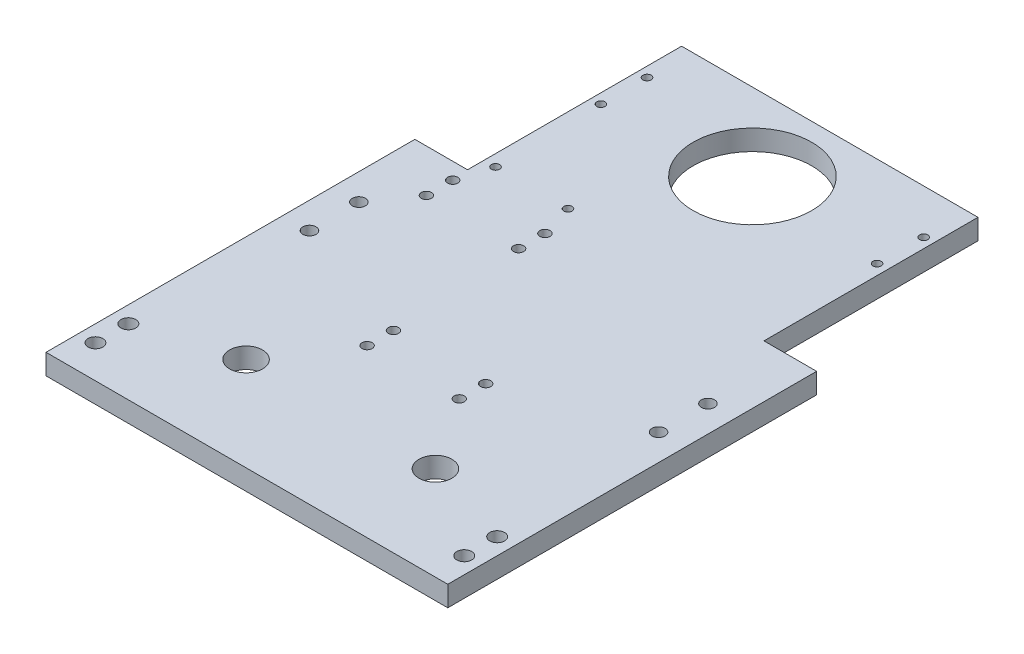
SolidWorks part; units mm, degrees
ref_plane "Front Plane" through (0, 0, 0) normal (0, 0, 1) x (1, 0, 0)
ref_plane "Top Plane" through (0, 0, 0) normal (0, 1, 0) x (1, 0, 0)
ref_plane "Right Plane" through (0, 0, 0) normal (1, 0, 0) x (0, 0, -1)
sketch "Sketch1" plane through (0, 0, 0) normal (0, 1, 0) x (1, 0, 0)
  line L1 (-61, 56) -> (61, 56)
  line L2 (-61, 56) -> (-61, -56)
  line L3 (-61, -56) -> (61, -56)
  line L4 (61, 56) -> (61, -56)
  line L5 (-61, 56) -> (61, -56) construction
  line L6 (-61, -56) -> (61, 56) construction
  point P0 (0, 0)
  dimension "D1" = 122
  dimension "D2" = 112
extrude "Boss-Extrude1" add sketch "Sketch1" along normal blind 6.2
sketch "Sketch2" plane through (0, 0, 0) normal (0, 1, 0) x (1, 0, 0)
  line L0 (61, 56) -> (-61, 56) construction
  line L1 (-45, 56) -> (45, 56)
  line L2 (-45, 56) -> (-45, 121)
  line L3 (-45, 121) -> (45, 121)
  line L4 (45, 56) -> (45, 121)
  line L5 (0, -55) -> (0, 55) construction
  dimension "D1" = 90
  dimension "D2" = 45
  dimension "D3" = 65
extrude "Boss-Extrude2" add sketch "Sketch2" along normal blind 6.2
sketch "Sketch3" plane through (0, 6.2, 0) normal (0, 1, 0) x (1, 0, 0)
  line L0 (-45, 56) -> (45, 56) construction
  line L1 (-45, 121) -> (-45, 56) construction
  line L2 (45, 56) -> (45, 121) construction
  line L3 (0, -3.41) -> (0, 3.41) construction
  circle A0 centre (-41.5, 61) radius 1.25
  circle A1 centre (-19.5, 61) radius 1.25
  circle A2 centre (-42, 93.5) radius 1.25
  circle A3 centre (-42, 107.5) radius 1.25
  circle A4 centre (42, 107.5) radius 1.25
  circle A5 centre (41.8595, 93.5) radius 1.25
  circle A6 centre (0, 97.5) radius 18
  dimension "D1" = 2.5
  dimension "D2" = 2.5
  dimension "D8" = 2.5
  dimension "D13" = 2.5
  dimension "D14" = 2.5
  dimension "D16" = 2.5
  dimension "D17" = 36
  dimension "D3" = 5
  dimension "D4" = 5
  dimension "D5" = 22
  dimension "D6" = 3.5
  dimension "D7" = 3
  dimension "D9" = 3
  dimension "D10" = 37.5
  dimension "D11" = 14
  dimension "D12" = 3
  dimension "D15" = 14
  dimension "D18" = 41.5
  dimension "D19" = 37.5
extrude "Cut-Extrude1" cut sketch "Sketch3" against normal through all
sketch "Sketch4" plane through (0, 6.2, 0) normal (0, 1, 0) x (1, 0, 0)
  line L0 (-41.5, 61) -> (-19.5, 61) construction
  line L1 (-30.5, 61) -> (-30.5, 13.896) construction
  line L2 (-45, 56) -> (-61, 56) construction
  line L3 (61, 56) -> (45, 56) construction
  line L4 (0, -3.41) -> (0, 3.41) construction
  circle A0 centre (-44.5, 51) radius 1.55
  circle A1 centre (-16.5, 51) radius 1.55
  circle A2 centre (-16.5, 43) radius 1.55
  circle A3 centre (-44.5, 43) radius 1.55
  circle A4 centre (-14, 2.5) radius 1.55
  circle A5 centre (14, 2.5) radius 1.55
  circle A6 centre (14, -5.5) radius 1.55
  circle A7 centre (-14, -5.5) radius 1.55
  dimension "D1" = 3.1
  dimension "D8" = 3.1
  dimension "D2" = 5
  dimension "D5" = 53.5
  dimension "D9" = 14
  dimension "D10" = 14
  dimension "D3" = 2
  dimension "D4" = 2
  dimension "D6" = 2
  dimension "D7" = 2
extrude "Cut-Extrude2" cut sketch "Sketch4" against normal through all
sketch "Sketch5" plane through (0, 6.2, 0) normal (0, 1, 0) x (1, 0, 0)
  line L0 (-61, 56) -> (-61, -56) construction
  line L1 (-45, 56) -> (-61, 56) construction
  line L2 (0, -3.41) -> (0, 3.41) construction
  circle A0 centre (-53, 31) radius 2
  circle A1 centre (-53, 16) radius 2
  circle A2 centre (53, 16) radius 2
  circle A3 centre (53, 31) radius 2
  dimension "D3" = 4
  dimension "D4" = 4
  dimension "D1" = 8
  dimension "D2" = 8
  dimension "D5" = 15
  dimension "D6" = 25
extrude "Cut-Extrude3" cut sketch "Sketch5" against normal blind 10
sketch "Sketch6" plane through (0, 6.2, 0) normal (0, 1, 0) x (1, 0, 0)
  line L0 (0, 55.945) -> (0, -50.7895) construction
  line L1 (0, -3.41) -> (0, 3.41) construction
  line L2 (-28.75, -27.5) -> (28.75, -27.5) construction
  line L3 (61, 56) -> (45, 56) construction
  circle A0 centre (-28.75, -27.5) radius 5
  circle A1 centre (28.75, -27.5) radius 5
  dimension "D4" = 10
  dimension "D5" = 10
  dimension "D1" = 83.5
  dimension "D2" = 28.75
  dimension "D3" = 28.75
extrude "Cut-Extrude4" cut sketch "Sketch6" against normal blind 10
sketch "Sketch7" plane through (0, 6.2, 0) normal (0, 1, 0) x (1, 0, 0)
  line L0 (-61, 56) -> (-61, -56) construction
  line L1 (-61, -56) -> (61, -56) construction
  line L2 (0, -3.41) -> (0, 3.41) construction
  circle A0 centre (-56, -36) radius 2.25
  circle A1 centre (-56, -46) radius 2.25
  circle A2 centre (56, -46) radius 2.25
  circle A3 centre (56, -36) radius 2.25
  point P6 (0, 0)
  point P8 (-55.8254, -54.5422)
  dimension "D2" = 5
  dimension "D5" = 4.5
  dimension "D6" = 4.5
  dimension "D1" = 5
  dimension "D3" = 10
  dimension "D4" = 10
extrude "Cut-Extrude5" cut sketch "Sketch7" against normal through all
equation "\"D2@Sketch2\"=\"D1@Sketch2\"/2"
equation "\"D2@Sketch3\"=\"D1@Sketch3\""
equation "\"D4@Sketch3\"=\"D3@Sketch3\""
equation "\"D13@Sketch3\"=\"D16@Sketch3\""
equation "\"D14@Sketch3\"=\"D13@Sketch3\""
equation "\"D8@Sketch3\"=\"D2@Sketch3\""
equation "\"D7@Sketch3\"=\"D9@Sketch3\""
equation "\"D16@Sketch3\"=\"D8@Sketch3\""
equation "\"D19@Sketch3\"=\"D10@Sketch3\""
equation "\"D8@Sketch4\"=\"D1@Sketch4\""
equation "\"D6@Sketch7\"=\"D5@Sketch7\""
